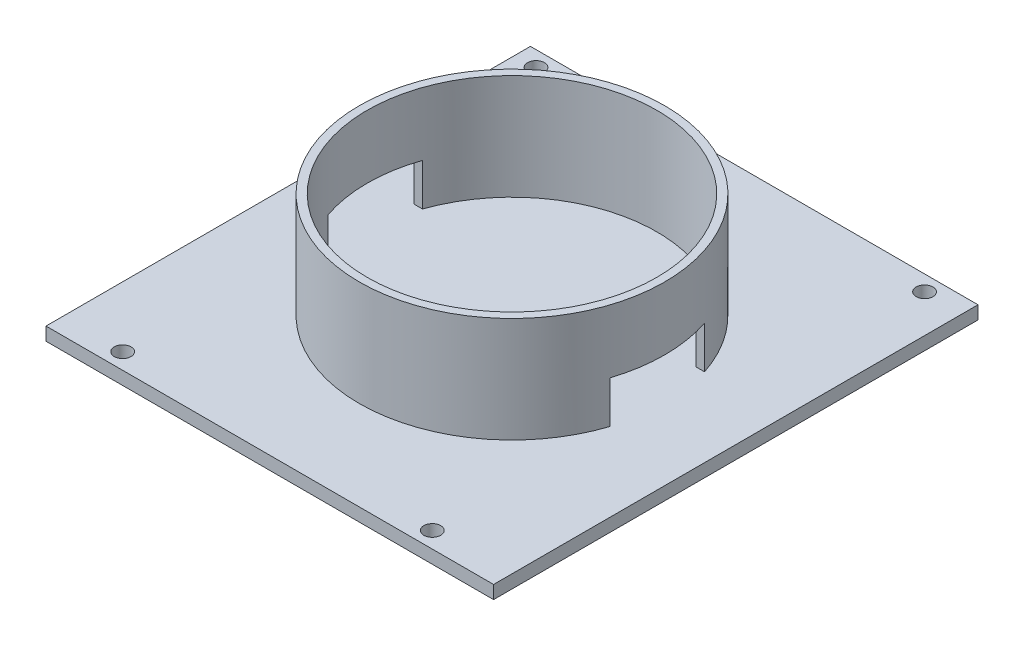
SolidWorks part; units mm, degrees
ref_plane "前视基准面" through (0, 0, 0) normal (0, 0, 1) x (1, 0, 0)
ref_plane "上视基准面" through (0, 0, 0) normal (0, 1, 0) x (1, 0, 0)
ref_plane "右视基准面" through (0, 0, 0) normal (1, 0, 0) x (0, 0, -1)
other "Configuration Table"
sketch "草图2" plane through (0, 0, 0) normal (0, 1, 0) x (1, 0, 0)
  line L0 (-42.5, 21.3368) -> (42.5, 21.3368)
  line L2 (32.5, -70.6632) -> (-32.5, -70.6632)
  line L4 (0, 21.3368) -> (0, 0) construction
  line L5 (0, -70.6632) -> (0, 0) construction
  line L6 (-42.5, 21.3368) -> (-42.5, -70.6632)
  line L7 (-42.5, -70.6632) -> (-32.5, -70.6632)
  line L8 (32.5, -70.6632) -> (42.5, -70.6632)
  line L9 (42.5, -70.6632) -> (42.5, 21.3368)
  dimension "D1" = 85
  dimension "D2" = 65
  dimension "D3" = 92
extrude "凸台-拉伸1" add sketch "草图2" along normal blind 2.5
sketch "草图4" plane through (0, 2.5, 0) normal (0, 1, 0) x (1, 0, 0)
  line L0 (-38.5, 18.3936) -> (35.3, 18.3936) construction
  line L2 (-31, -67.6064) -> (27.8, -67.6064) construction
  circle A0 centre (-38.5, 18.3936) radius 1.6
  circle A1 centre (35.3, 18.3936) radius 1.6
  circle A2 centre (-31, -67.6064) radius 1.6
  circle A3 centre (27.8, -67.6064) radius 1.6
  point P8 (0, 0)
  dimension "D1" = 3.2
  dimension "D2" = 3.2
  dimension "D3" = 3.2
  dimension "D4" = 3.2
  dimension "D5" = 27.8
  dimension "D6" = 35.3
  dimension "D7" = 86
extrude "切除-拉伸1" cut sketch "草图4" against normal blind 2.5
sketch "草图6" plane through (0, 2.5, 0) normal (0, 1, 0) x (1, 0, 0)
  line L0 (-42.5, 21.3368) -> (-42.5, -70.6632) construction
  line L1 (-42.5, -24.6632) -> (0, -24.6632) construction
  line L2 (0, 0) -> (0, -24.6632) construction
  circle A0 centre (0, -24.6632) radius 27.5
  circle A1 centre (0, -24.6632) radius 29
  dimension "D1" = 55
  dimension "D2" = 58
extrude "凸台-拉伸2" add sketch "草图6" along normal blind 20
ref_plane "基准面1" through (0, 0, 0) normal (1, 0, 0) x (0, 0, -1)
sketch "草图7" plane through (0, 0, 0) normal (1, 0, 0) x (0, 0, -1)
  line L0 (-70.6632, 2.5) -> (21.3368, 2.5) construction
  line L1 (-33.6632, 2.5) -> (-15.6632, 2.5)
  line L2 (-33.6632, 2.5) -> (-33.6632, 10.5)
  line L3 (-33.6632, 10.5) -> (-15.6632, 10.5)
  line L4 (-15.6632, 2.5) -> (-15.6632, 10.5)
  line L5 (-70.6632, 2.5) -> (-70.6632, 0) construction
  line L6 (21.3368, 2.5) -> (21.3368, 0) construction
  dimension "D1" = 18
  dimension "D2" = 92
  dimension "D3" = 37
  dimension "D4" = 37
  dimension "D5" = 8
extrude "切除-拉伸2" cut sketch "草图7" against normal through all and the other way through all
